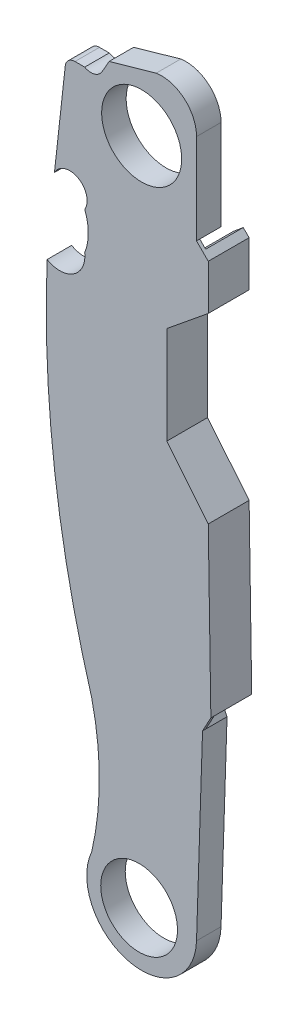
SolidWorks part; units mm, degrees
material "Acrylic (Medium-high impact)"
ref_plane "Front Plane" through (0, 0, 0) normal (0, 0, 1) x (1, 0, 0)
ref_plane "Top Plane" through (0, 0, 0) normal (0, 1, 0) x (1, 0, 0)
ref_plane "Right Plane" through (0, 0, 0) normal (1, 0, 0) x (0, 0, -1)
sketch "Sketch1" plane through (0, 0, 0) normal (0, 0, 1) x (1, 0, 0)
  line L0 (-30.2631, 19.6091) -> (47.5496, 19.6091) construction
  line L1 (11.4551, 2.1717) -> (10.9887, -12.1944)
  line L2 (11.4551, 2.1717) -> (12.103, 3.3727)
  line L3 (12.103, 3.3727) -> (11.9008, 16.3262)
  line L4 (11.9008, 16.3262) -> (8.6738, 20.285)
  line L5 (8.6738, 20.285) -> (8.6738, 27.865)
  line L6 (8.6738, 27.865) -> (11.9008, 30.4955)
  line L7 (11.9008, 34.009) -> (11.9008, 30.4955)
  line L8 (11.9008, 34.009) -> (10.9887, 34.9211)
  line L9 (10.9887, 34.9211) -> (10.9887, 41.9475)
  line L10 (7.8584, 44.6526) -> (4.1932, 43.6083)
  line L11 (4.1932, 43.6083) -> (3.6576, 42.6607)
  line L12 (2.2965, 42.2778) -> (0.8585, 42.2778)
  line L13 (0.8585, 42.2778) -> (-0.0545, 34.009)
  arc A0 (-0.6254, 27.865) -> (2.8357, 0.1093) centre (85.2899, 24.4849) ccw
  arc A1 (2.8357, 0.1093) -> (2.8357, -10.2938) centre (-19.4776, -5.0922) cw
  arc A2 (2.8357, -10.2938) -> (10.9887, -12.1944) centre (6.7225, -12.0581) ccw
  arc A3 (10.9887, 41.9475) -> (7.8584, 44.6526) centre (8.2547, 41.9475) ccw
  arc A4 (3.6576, 42.6607) -> (2.2965, 42.2778) centre (2.7843, 43.1543) cw
  arc A5 (-0.0545, 34.009) -> (2.2965, 32.6925) centre (1.1348, 33.3754) cw
  arc A6 (-0.6254, 27.865) -> (2.2965, 29.7885) centre (0.356, 29.5552) ccw
  arc A7 (2.2965, 32.6925) -> (2.2965, 29.7885) centre (-1.3152, 31.2405) cw
  circle A8 centre (6.7225, 39.8602) radius 3.1115
  circle A9 centre (6.5257, -12.2034) radius 2.9845
extrude "Boss-Extrude1" add sketch "Sketch1" along normal blind 1.905
sketch "Sketch7" plane through (0, 0, 0) normal (0, 0, -1) x (-1, 0, 0)
  line L0 (608.2646, 1483.0494) -> (3296.2646, 1483.0494) construction
  line L4 (-12.103, 3.3727) -> (-11.4551, 2.1717)
  line L5 (-10.9887, 34.9211) -> (-11.4447, 34.465)
  arc A4 (-7.1394, 27.7408) -> (-12.103, 3.3727) centre (-53.3794, 24.47) cw
  arc A5 (-6.1172, 27.4194) -> (-11.4551, 2.1717) centre (-52.0057, 23.9331) cw
  arc A6 (-7.1394, 27.7408) -> (-11.4447, 34.465) centre (-18.5778, 25.1575) ccw
  arc A7 (-6.1172, 27.4194) -> (-10.9887, 34.9211) centre (-16.447, 26.044) ccw
  dimension "D1" = 10.4209
  dimension "D2" = 11.7265
  dimension "D3" = 46.0208
  dimension "D4" = 46.3555
  dimension "D5" = 0.6449
  dimension "D6" = 1.3646
extrude "Cut-Extrude1" cut sketch "Sketch7" against normal blind 1.651
sketch "Sketch8" plane through (0, 0, 0) normal (0, 0, -1) x (-1, 0, 0)
  line L6 (-11.9008, 16.3262) -> (-12.103, 3.3727)
  line L7 (-11.4447, 34.465) -> (-11.9008, 34.009)
  line L8 (-11.9008, 34.009) -> (-11.9008, 30.4955)
  line L9 (-11.9008, 30.4955) -> (-8.6738, 27.865)
  line L10 (-8.6738, 27.865) -> (-8.6738, 20.285)
  line L11 (-8.6738, 20.285) -> (-11.9008, 16.3262)
  line L12 (-11.9008, 16.3262) -> (-12.103, 3.3727)
  line L13 (-11.4447, 34.465) -> (-11.9008, 34.009)
  line L14 (-11.9008, 34.009) -> (-11.9008, 30.4955)
  line L15 (-11.9008, 30.4955) -> (-8.6738, 27.865)
  line L16 (-8.6738, 27.865) -> (-8.6738, 20.285)
  line L17 (-8.6738, 20.285) -> (-11.9008, 16.3262)
  arc A2 (-12.103, 3.3727) -> (-7.1394, 27.7408) centre (-53.3794, 24.47) ccw
  arc A3 (-7.1394, 27.7408) -> (-11.4447, 34.465) centre (-18.5778, 25.1575) ccw
  arc A4 (-12.103, 3.3727) -> (-7.1394, 27.7408) centre (-53.3794, 24.47) ccw
  arc A5 (-7.1394, 27.7408) -> (-11.4447, 34.465) centre (-18.5778, 25.1575) ccw
  dimension "D1" = 0
extrude "Boss-Extrude2" add sketch "Sketch8" along normal blind 1.27 contours A4 A5 L13 L14 L15 L16 L17 L12
fillet "Fillet1" radius 0.762 1 edges at (0.8585, 42.2778, 0.9525)
scale "Scale1" scale about centroid uniform scaling yes scale factor 1.035084
